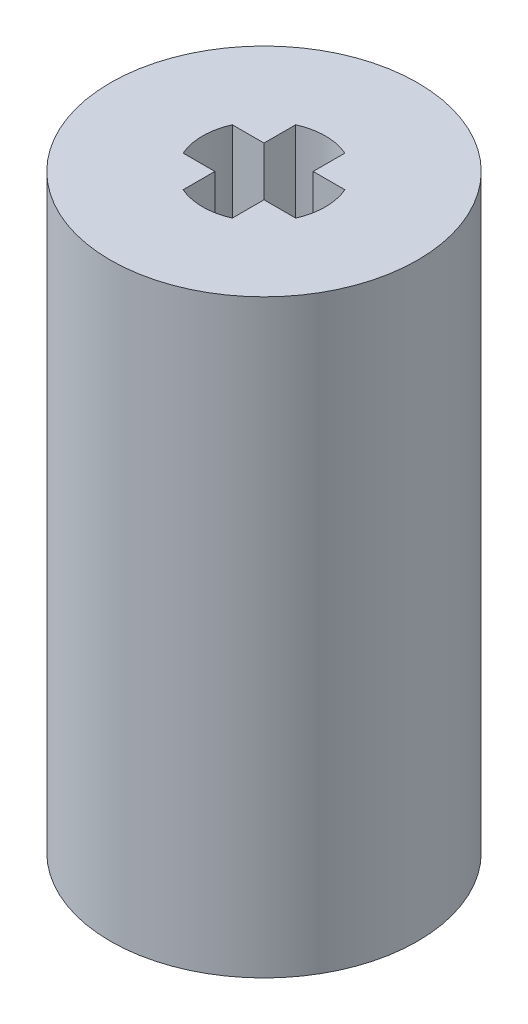
SolidWorks part; units mm, degrees
ref_plane "Plan de face" through (0, 0, 0) normal (0, 0, 1) x (1, 0, 0)
ref_plane "Plan de dessus" through (0, 0, 0) normal (0, 1, 0) x (1, 0, 0)
ref_plane "Plan de droite" through (0, 0, 0) normal (1, 0, 0) x (0, 0, -1)
sketch "Esquisse1" plane through (0, 0, 0) normal (0, 1, 0) x (1, 0, 0)
  circle A0 centre (0, 0) radius 6.25
  dimension "D1" = 12.5
extrude "Boss.-Extru.1" add sketch "Esquisse1" along normal blind 24 contours A0
sketch "Esquisse4" plane through (0, 0, 0) normal (0, -1, 0) x (1, 0, 0)
  line L0 (1.6716, 3.075) -> (1.6716, -3.075)
  line L1 (0, 0) -> (1.6716, 0) construction
  line L2 (0, 0) -> (0, 3.5) construction
  line L3 (0, 0) -> (-3.5, 0) construction
  arc A1 (1.6716, -3.075) -> (1.6716, 3.075) centre (0, 0) cw
  point P7 (1.6716, 3.075)
  dimension "D1" = 6.15
  dimension "D2" = 3.5
  dimension "D3" = 1.6716
extrude "Enlèv. mat.-Extru.1" cut sketch "Esquisse4" against normal blind 12
sketch "Esquisse5" plane through (0, 24, 0) normal (0, 1, 0) x (1, 0, 0)
  line L0 (0, 0) -> (-2.5, 0) construction
  line L1 (0, 0) -> (0, 2.5) construction
  line L2 (1, -2.2913) -> (1, 2.2913)
  line L3 (0, 0) -> (2.5, 0) construction
  line L4 (-1, -2.2913) -> (-1, 2.2913)
  line L5 (0, 0) -> (0, -2.5) construction
  line L6 (0, 0) -> (0, 6.25) construction
  line L7 (-2.2913, -1) -> (2.2913, -1)
  line L8 (0, 0) -> (0, -6.25) construction
  line L9 (-2.2913, 1) -> (2.2913, 1)
  circle A0 centre (0, 0) radius 6.25 construction
  arc A1 (-2.2913, 1) -> (-2.2913, -1) centre (0, 0) ccw
  arc A2 (-1, 2.2913) -> (1, 2.2913) centre (0, 0) cw
  arc A3 (2.2913, 1) -> (2.2913, -1) centre (0, 0) cw
  arc A4 (1, -2.2913) -> (-1, -2.2913) centre (0, 0) cw
  point P17 (0, 0)
  point P22 (0, 0)
  point P24 (0, 0)
  point P25 (2.3646, 1)
  dimension "D1" = 2.5
  dimension "D6" = 1
  dimension "D8" = 2.5
  dimension "D5" = 2.5
  dimension "D9" = 2.5
  dimension "D10" = 2.5
  dimension "D11" = 2.5
  dimension "D2" = 2.5
  dimension "D3" = 1
  dimension "D4" = 1
  dimension "D7" = 2.5
extrude "Enlèv. mat.-Extru.3" cut sketch "Esquisse5" against normal blind 10 contours A2 L4 L9 L2 | A3 L9 L2 L7 | L9 A1 L7 L4 | A4 L2 L7 L4 | L9 L4 L7 L2
equation "\"1.50tenon\"=1.5"
